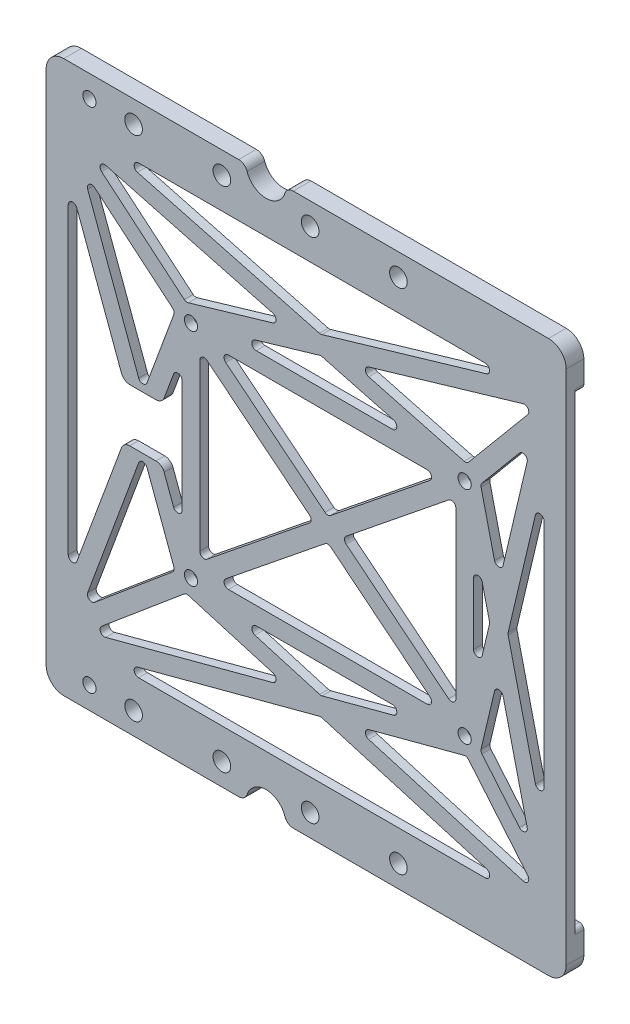
SolidWorks part; units mm, degrees
material "Thornel Mat VMA"
ref_plane "前视基准面" through (0, 0, 0) normal (0, 0, 1) x (1, 0, 0)
ref_plane "上视基准面" through (0, 0, 0) normal (0, 1, 0) x (1, 0, 0)
ref_plane "右视基准面" through (0, 0, 0) normal (1, 0, 0) x (0, 0, -1)
other "Configuration Table"
sketch "草图1" plane through (0, 0, 0) normal (0, 0, 1) x (1, 0, 0)
  line L0 (-59, 57.5) -> (-49, 57.5) construction
  line L1 (-59, -62.5) -> (59, -62.5)
  line L2 (-59, -62.5) -> (-59, 62.5)
  line L3 (-59, 62.5) -> (59, 62.5)
  line L4 (59, -62.5) -> (59, 62.5)
  line L5 (-59, -62.5) -> (59, 62.5) construction
  line L6 (-59, 62.5) -> (59, -62.5) construction
  line L7 (-49, 57.5) -> (-39, 57.5) construction
  line L8 (-39, 57.5) -> (-19, 57.5) construction
  line L9 (-19, 57.5) -> (1, 57.5) construction
  line L10 (0, 0) -> (149.8552, 0) construction
  line L11 (-19, -57.5) -> (1, -57.5) construction
  line L12 (-39, -57.5) -> (-19, -57.5) construction
  line L13 (-49, -57.5) -> (-39, -57.5) construction
  line L14 (1, 57.5) -> (21, 57.5) construction
  circle A0 centre (-49, 57.5) radius 1.5
  circle A1 centre (-39, 57.5) radius 2
  circle A2 centre (-19, 57.5) radius 2
  circle A3 centre (1, 57.5) radius 2
  circle A4 centre (1, -57.5) radius 2
  circle A5 centre (-19, -57.5) radius 2
  circle A6 centre (-39, -57.5) radius 2
  circle A7 centre (-49, -57.5) radius 1.5
  circle A8 centre (21, 57.5) radius 2
  circle A9 centre (21, -57.5) radius 2
  point P0 (0, 0)
  dimension "D6" = 4
  dimension "D7" = 3
  dimension "D1" = 118
  dimension "D2" = 125
  dimension "D3" = 10
  dimension "D4" = 10
  dimension "D5" = 5
  dimension "D8" = 20
extrude "凸台-拉伸1" add sketch "草图1" along normal blind 4
sketch "草图2" plane through (0, 0, 0) normal (0, 0, -1) x (-1, 0, 0)
  line L0 (59, -62.5) -> (-59, -62.5) construction
  line L1 (59, 62.5) -> (58.8, 62.5)
  line L2 (59, 62.5) -> (59, -62.5)
  line L3 (59, -62.5) -> (58.8, -62.5)
  line L4 (58.8, 62.5) -> (58.8, -62.5)
  line L5 (-1, 57.5) -> (19, 57.5) construction
  line L6 (9, 57.5) -> (9, 62.5) construction
  line L7 (-59, 62.5) -> (59, 62.5) construction
  line L8 (0, 0) -> (86.8902, 0) construction
  line L9 (9, -57.5) -> (9, -62.5) construction
  circle A0 centre (9, 62.5) radius 4.5
  circle A1 centre (9, -62.5) radius 4.5
  dimension "D2" = 9
  dimension "D1" = 0.2
extrude "切除-拉伸1" cut sketch "草图2" against normal up to surface (4 mm away) up to face at (0, 0, 4)
sketch "草图3" plane through (0, 0, 0) normal (0, 0, -1) x (-1, 0, 0)
  line L0 (0, 0) -> (-5, 0) construction
  line L5 (-36, -25) -> (26, -25) construction
  line L6 (-36, -25) -> (-36, 25) construction
  line L7 (-36, 25) -> (26, 25) construction
  line L8 (26, -25) -> (26, 25) construction
  line L9 (-36, -25) -> (26, 25) construction
  line L10 (-36, 25) -> (26, -25) construction
  circle A0 centre (26, 25) radius 1.5
  circle A1 centre (26, -25) radius 1.5
  circle A2 centre (-36, -25) radius 1.5
  circle A3 centre (-36, 25) radius 1.5
  point P0 (-5, 0)
  dimension "D4" = 3
  dimension "D1" = 62
  dimension "D2" = 50
  dimension "D3" = 5
extrude "切除-拉伸2" cut sketch "草图3" against normal up to surface (4 mm away) up to face at (-4.45, 0, 4)
fillet "圆角1" radius 2 4 edges at (-4.5, 62.5, 2) (-13.5, 62.5, 2) (-13.5, -62.5, 2) (-4.5, -62.5, 2)
fillet "圆角2" radius 4 4 edges at (59, 62.5, 2) (59, -62.5, 2) (-58.8, -62.5, 2) (-58.8, 62.5, 2)
sketch "草图4" plane through (0, 0, 0) normal (0, 0, -1) x (-1, 0, 0)
  line L0 (-59, -58.5) -> (-59, 58.5) construction
  line L3 (-59, 52.5) -> (58.8, 52.5)
  line L4 (-59, 52.5) -> (-59, -52.5)
  line L6 (-59, -52.5) -> (58.8, -52.5)
  line L7 (58.8, 52.5) -> (58.8, -52.5)
  line L8 (58.8, 58.5) -> (58.8, -58.5) construction
  line L9 (15.1847, 62.5) -> (54.8, 62.5) construction
  line L10 (54.8, -62.5) -> (15.1847, -62.5) construction
  dimension "D1" = 10
  dimension "D2" = 10
extrude "切除-拉伸3" cut sketch "草图4" against normal blind 2
sketch "草图5" plane through (0, 0, 2) normal (0, 0, -1) x (-1, 0, 0)
  line L0 (26, -25) -> (-36, 25) construction
  line L1 (-36, 25) -> (26, 25) construction
  line L2 (26, 25) -> (-36, -25) construction
  line L3 (-36, -25) -> (26, -25) construction
  line L4 (26, -25) -> (58.8, -52.5) construction
  line L5 (26, -25) -> (26, 25) construction
  line L6 (26, 25) -> (58.8, 52.5) construction
  line L7 (58.8, 52.5) -> (-59, 52.5) construction
  line L8 (-59, 52.5) -> (-36, 25) construction
  line L9 (-36, 25) -> (-36, -25) construction
  line L10 (-36, -25) -> (-59, -52.5) construction
  line L12 (-59, 52.5) -> (-59, -52.5) construction
  line L13 (-59, -49.3826) -> (-38, -24.2739)
  line L14 (-38, -24.2739) -> (-38, 24.2739)
  line L15 (-38, 24.2739) -> (-59, 49.3826)
  line L16 (-54.72, 50.5) -> (-35.0654, 27)
  line L17 (-35.0654, 27) -> (25.2725, 27)
  line L18 (25.2725, 27) -> (53.3016, 50.5)
  line L19 (53.3016, 50.5) -> (-54.72, 50.5)
  line L20 (28, 24.0669) -> (53.8, 45.698)
  line L21 (53.8, 45.698) -> (53.8, -45.698)
  line L22 (53.8, -45.698) -> (28, -24.0669)
  line L23 (28, -24.0669) -> (28, 24.0669)
  line L24 (53.3016, -50.5) -> (25.2725, -27)
  line L25 (25.2725, -27) -> (-35.0654, -27)
  line L26 (-35.0654, -27) -> (-54.72, -50.5)
  line L27 (-54.72, -50.5) -> (53.3016, -50.5)
  line L28 (-30.334, -23) -> (-5, -2.5693)
  line L29 (-5, -2.5693) -> (20.334, -23)
  line L30 (20.334, -23) -> (-30.334, -23)
  line L31 (24, 20.8178) -> (24, -20.8178)
  line L32 (24, -20.8178) -> (-1.814, 0)
  line L33 (-1.814, 0) -> (24, 20.8178)
  line L34 (-54, 43.4043) -> (-54, -43.4043)
  line L35 (58.8, -52.5) -> (58.8, 52.5) construction
  line L36 (-59, -52.5) -> (58.8, -52.5) construction
  line L37 (-5, 0) -> (64.3357, 0) construction
  line L38 (-5, 0) -> (-5, -44.1109) construction
  line L39 (-34, -20.8178) -> (-8.186, 0)
  line L40 (-8.186, 0) -> (-34, 20.8178)
  line L41 (-34, 20.8178) -> (-34, -20.8178)
  line L42 (-30.334, 23) -> (-5, 2.5693)
  line L43 (20.334, 23) -> (-30.334, 23)
  line L44 (-5, 2.5693) -> (20.334, 23)
  dimension "D1" = 2
  dimension "D2" = 2
  dimension "D3" = 2
  dimension "D4" = 2
  dimension "D5" = 2
  dimension "D6" = 2
  dimension "D7" = 2
  dimension "D8" = 2
  dimension "D9" = 2
  dimension "D10" = 5
  dimension "D11" = 5
  dimension "D12" = 2
  dimension "D13" = 2
  dimension "D14" = 2
  dimension "D15" = 2
  dimension "D16" = 2
  dimension "D17" = 2
  dimension "D18" = 2
  dimension "D19" = 2
  dimension "D20" = 2
  dimension "D21" = 2
  dimension "D22" = 2
extrude "切除-拉伸4" cut sketch "草图5" against normal blind 2 contours L26 L27 L24 L25 | L15 L34 L13 L14 | L18 L19 L16 L17 | L23 L22 L21 L20 | L40 L41 L39 | L42 L44 L43 | L33 L32 L31 | L30 L29 L28
sketch "草图6" plane through (0, 0, 2) normal (0, 0, -1) x (-1, 0, 0)
  line L0 (53.8, 45.698) -> (28, -24.0669) construction
  line L1 (28, -24.0669) -> (28, 24.0669) construction
  line L2 (28, 24.0669) -> (53.8, -45.698) construction
  line L3 (53.3016, -50.5) -> (-35.0654, -27) construction
  line L4 (-35.0654, -27) -> (25.2725, -27) construction
  line L5 (53.3016, -50.5) -> (25.2725, -27) construction
  line L7 (25.2725, -27) -> (-54.72, -50.5) construction
  line L8 (-36, -25) -> (26, 25) construction
  line L9 (-5, 0) -> (78.3704, 0) construction
  line L10 (-54, -43.4043) -> (-38, 24.2739) construction
  line L11 (-38, 24.2739) -> (-38, -24.2739) construction
  line L12 (-38, -24.2739) -> (-54, 43.4043) construction
  line L13 (-51.135, 39.9788) -> (-43.7387, 8.693)
  line L14 (-38, 24.2739) -> (-54, 43.4043) construction
  line L15 (-43.7387, 8.693) -> (-39.6022, 26.1896)
  line L16 (-39.6022, 26.1896) -> (-51.135, 39.9788)
  line L17 (-54, 34.7113) -> (-54, -34.7113)
  line L18 (-54, -34.7113) -> (-45.7938, 0)
  line L19 (-45.7938, 0) -> (-54, 34.7113)
  line L20 (-54, 43.4043) -> (-54, -43.4043) construction
  line L21 (28, 18.3008) -> (34.7679, 0)
  line L22 (-41.6835, 0) -> (-38, 15.5809)
  line L23 (-38, 15.5809) -> (-38, -15.5809)
  line L24 (-38, -15.5809) -> (-41.6835, 0)
  line L25 (34.7679, 0) -> (28, -18.3008)
  line L26 (28, -18.3008) -> (28, 18.3008)
  line L27 (29.6277, 25.4316) -> (36.9003, 5.7661)
  line L28 (28, 24.0669) -> (53.8, 45.698) construction
  line L29 (36.9003, 5.7661) -> (50.7093, 43.1067)
  line L30 (50.7093, 43.1067) -> (29.6277, 25.4316)
  line L31 (39.0326, 0) -> (53.8, 39.9319)
  line L32 (53.8, 45.698) -> (53.8, -45.698) construction
  line L33 (53.8, 39.9319) -> (53.8, -39.9319)
  line L34 (53.8, -39.9319) -> (39.0326, 0)
  line L35 (-27.2834, -27) -> (-3.4226, -33.3455)
  line L36 (-3.4226, -33.3455) -> (18.1769, -27)
  line L37 (18.1769, -27) -> (-27.2834, -27)
  line L38 (-36.4814, -28.693) -> (-10.8175, -35.5179)
  line L39 (-35.0654, -27) -> (-54.72, -50.5) construction
  line L40 (-10.8175, -35.5179) -> (-52.4087, -47.7365)
  line L41 (-52.4087, -47.7365) -> (-36.4814, -28.693)
  line L42 (4.0259, -35.3263) -> (27.1137, -28.5436)
  line L43 (27.1137, -28.5436) -> (49.6866, -47.4691)
  line L44 (49.6866, -47.4691) -> (4.0259, -35.3263)
  line L45 (-47.6244, -50.5) -> (-3.369, -37.4987)
  line L46 (-54.72, -50.5) -> (53.3016, -50.5) construction
  line L47 (-3.369, -37.4987) -> (45.5196, -50.5)
  line L48 (45.5196, -50.5) -> (-47.6244, -50.5)
  line L49 (36.9003, -5.7661) -> (50.7093, -43.1067)
  line L50 (29.6277, -25.4316) -> (36.9003, -5.7661)
  line L51 (50.7093, -43.1067) -> (29.6277, -25.4316)
  line L52 (-39.6022, -26.1896) -> (-51.135, -39.9788)
  line L53 (-51.135, -39.9788) -> (-43.7387, -8.693)
  line L54 (-43.7387, -8.693) -> (-39.6022, -26.1896)
  line L55 (25.2725, 27) -> (-54.72, 50.5) construction
  line L56 (-35.0654, 27) -> (25.2725, 27) construction
  line L57 (53.3016, 50.5) -> (-35.0654, 27) construction
  line L58 (45.5196, 50.5) -> (-47.6244, 50.5)
  line L59 (-3.369, 37.4987) -> (45.5196, 50.5)
  line L60 (-47.6244, 50.5) -> (-3.369, 37.4987)
  line L61 (49.6866, 47.4691) -> (4.0259, 35.3263)
  line L62 (27.1137, 28.5436) -> (49.6866, 47.4691)
  line L63 (4.0259, 35.3263) -> (27.1137, 28.5436)
  line L64 (-52.4087, 47.7365) -> (-36.4814, 28.693)
  line L65 (-10.8175, 35.5179) -> (-52.4087, 47.7365)
  line L66 (-36.4814, 28.693) -> (-10.8175, 35.5179)
  line L67 (18.1769, 27) -> (-27.2834, 27)
  line L68 (-3.4226, 33.3455) -> (18.1769, 27)
  line L69 (-27.2834, 27) -> (-3.4226, 33.3455)
  line L73 (-1.814, 0) -> (24, -20.8178)
  line L74 (-35.0654, -27) -> (-54.72, -50.5)
  line L75 (25.2725, -27) -> (-35.0654, -27)
  line L76 (53.3016, -50.5) -> (25.2725, -27)
  line L77 (-54.72, -50.5) -> (53.3016, -50.5)
  line L78 (-35.0654, -27) -> (-54.72, -50.5)
  line L79 (25.2725, -27) -> (-35.0654, -27)
  line L80 (53.3016, -50.5) -> (25.2725, -27)
  line L81 (-54.72, -50.5) -> (53.3016, -50.5)
  line L82 (24, 20.8178) -> (-1.814, 0)
  line L83 (24, -20.8178) -> (24, 20.8178)
  line L84 (-1.814, 0) -> (24, -20.8178)
  line L85 (24, 20.8178) -> (-1.814, 0)
  line L86 (24, -20.8178) -> (24, 20.8178)
  line L87 (-30.334, 23) -> (-5, 2.5693)
  line L88 (20.334, 23) -> (-30.334, 23)
  line L89 (-5, 2.5693) -> (20.334, 23)
  line L90 (-30.334, 23) -> (-5, 2.5693)
  line L91 (20.334, 23) -> (-30.334, 23)
  line L92 (-5, 2.5693) -> (20.334, 23)
  line L93 (20.334, -23) -> (-5, -2.5693)
  line L94 (-30.334, -23) -> (20.334, -23)
  line L95 (-5, -2.5693) -> (-30.334, -23)
  line L96 (20.334, -23) -> (-5, -2.5693)
  line L97 (-30.334, -23) -> (20.334, -23)
  line L98 (-5, -2.5693) -> (-30.334, -23)
  line L99 (-8.186, 0) -> (-34, 20.8178)
  line L100 (25.2725, 27) -> (53.3016, 50.5)
  line L101 (-35.0654, 27) -> (25.2725, 27)
  line L102 (-54.72, 50.5) -> (-35.0654, 27)
  line L103 (53.3016, 50.5) -> (-54.72, 50.5)
  line L104 (25.2725, 27) -> (53.3016, 50.5)
  line L105 (-35.0654, 27) -> (25.2725, 27)
  line L106 (-54.72, 50.5) -> (-35.0654, 27)
  line L107 (53.3016, 50.5) -> (-54.72, 50.5)
  line L108 (-38, 24.2739) -> (-54, 43.4043)
  line L109 (-38, -24.2739) -> (-38, 24.2739)
  line L110 (-54, -43.4043) -> (-38, -24.2739)
  line L111 (-54, 43.4043) -> (-54, -43.4043)
  line L112 (-38, 24.2739) -> (-54, 43.4043)
  line L113 (-38, -24.2739) -> (-38, 24.2739)
  line L114 (-54, -43.4043) -> (-38, -24.2739)
  line L115 (-54, 43.4043) -> (-54, -43.4043)
  line L116 (28, -24.0669) -> (53.8, -45.698)
  line L117 (28, 24.0669) -> (28, -24.0669)
  line L118 (53.8, 45.698) -> (28, 24.0669)
  line L119 (53.8, -45.698) -> (53.8, 45.698)
  line L120 (28, -24.0669) -> (53.8, -45.698)
  line L121 (28, 24.0669) -> (28, -24.0669)
  line L122 (53.8, 45.698) -> (28, 24.0669)
  line L123 (53.8, -45.698) -> (53.8, 45.698)
  line L124 (-34, -20.8178) -> (-8.186, 0)
  line L125 (-34, 20.8178) -> (-34, -20.8178)
  line L126 (-8.186, 0) -> (-34, 20.8178)
  line L127 (-34, -20.8178) -> (-8.186, 0)
  line L128 (-34, 20.8178) -> (-34, -20.8178)
  circle A1 centre (26, 25) radius 1.5
  circle A2 centre (26, 25) radius 1.5
  circle A3 centre (-36, -25) radius 1.5
  circle A4 centre (-36, -25) radius 1.5
  circle A5 centre (-36, 25) radius 1.5
  circle A6 centre (-36, 25) radius 1.5
  circle A7 centre (26, -25) radius 1.5
  circle A8 centre (26, -25) radius 1.5
  point P45 (-49.8969, -17.3557)
  line M4 (-54, 43.4043) -> (-38, 24.2739)
  line M5 (-38, 24.2739) -> (-38, -24.2739)
  line M6 (-38, -24.2739) -> (-54, -43.4043)
  line M7 (-54, -43.4043) -> (-54, 43.4043)
  line M8 (53.3016, 50.5) -> (25.2725, 27)
  line M9 (25.2725, 27) -> (-35.0654, 27)
  line M10 (-35.0654, 27) -> (-54.72, 50.5)
  line M11 (-54.72, 50.5) -> (53.3016, 50.5)
  line M15 (-54.72, -50.5) -> (-35.0654, -27)
  line M16 (-35.0654, -27) -> (25.2725, -27)
  line M17 (25.2725, -27) -> (53.3016, -50.5)
  line M18 (53.3016, -50.5) -> (-54.72, -50.5)
  line M33 (53.8, -45.698) -> (28, -24.0669)
  line M34 (28, -24.0669) -> (28, 24.0669)
  line M35 (28, 24.0669) -> (53.8, 45.698)
  line M36 (53.8, 45.698) -> (53.8, -45.698)
  dimension "D1" = 2
  dimension "D2" = 2
  dimension "D3" = 2
  dimension "D4" = 2
  dimension "D5" = 2
  dimension "D6" = 2
  dimension "D7" = 2
  dimension "D8" = 2
  dimension "D9" = 2
  dimension "D10" = 2
  dimension "D11" = 2
  dimension "D12" = 2
  dimension "D13" = 2
  dimension "D14" = 2
  dimension "D15" = 0
  dimension "D16" = 0
  dimension "D17" = 0
  dimension "D18" = 0
  dimension "D19" = 0
  dimension "D20" = 0
  dimension "D21" = 0
  dimension "D22" = 0
  dimension "D23" = 0
  dimension "D24" = 0
  dimension "D25" = 0
  dimension "D26" = 0
extrude "凸台-拉伸2" add sketch "草图6" against normal blind 2 contours L69 L68 L63 L61 L59 L60 L65 L66 M9 M8 M11 M10 | L50 L49 L34 L31 L29 L27 L21 L25 M33 M36 M35 M34 | L45 L47 L44 L42 L36 L35 L38 L40 M18 M17 M16 M15 | L53 L54 L24 L22 L15 L13 L19 L18 M6 M5 M4 M7
fillet "圆角3" radius 1 64 edges at (-50.7093, -43.1067, 3) (-36.9003, -5.7661, 3) (-29.6277, -25.4316, 3) (5, -2.5693, 3) (30.334, -23, 3) (-20.334, -23, 3) (-24, -20.8178, 3) (-24, 20.8178, 3) (1.814, 0, 3) (59, 52.5, 1) (-58.8, 52.5, 1) (-58.8, -52.5, 1) (59, -52.5, 1) (5, 2.5693, 3) (-20.334, 23, 3) (30.334, 23, 3) (34, 20.8178, 3) (34, -20.8178, 3) (8.186, 0, 3) (3.369, 37.4987, 3) (-45.5196, 50.5, 3) (47.6244, 50.5, 3) (10.8175, 35.5179, 3) (52.4087, 47.7365, 3) (36.4814, 28.693, 3) (3.4226, 33.3455, 3) (27.2834, 27, 3) (-18.1769, 27, 3) (-4.0259, 35.3263, 3) (-27.1137, 28.5436, 3) (-49.6866, 47.4691, 3) (-39.0326, 0, 3) (-53.8, 39.9319, 3) (-36.9003, 5.7661, 3) (-50.7093, 43.1067, 3) (-29.6277, 25.4316, 3) (-34.7679, 0, 3) (-28, 18.3008, 3) (-28, -18.3008, 3) (3.369, -37.4987, 3) (47.6244, -50.5, 3) (-45.5196, -50.5, 3) (-4.0259, -35.3263, 3) (-49.6866, -47.4691, 3) (-27.1137, -28.5436, 3) (3.4226, -33.3455, 3) (-18.1769, -27, 3) (27.2834, -27, 3) (10.8175, -35.5179, 3) (36.4814, -28.693, 3) (52.4087, -47.7365, 3) (45.7938, 0, 3) (54, 34.7113, 3) (54, -34.7113, 3) (43.7387, -8.693, 3) (51.135, -39.9788, 3) (39.6022, -26.1896, 3) (41.6835, 0, 3) (38, -15.5809, 3) (38, 15.5809, 3) (43.7387, 8.693, 3) (39.6022, 26.1896, 3) (51.135, 39.9788, 3) (-53.8, -39.9319, 3)
sketch "草图7" plane through (0, 0, 2) normal (0, 0, -1) x (-1, 0, 0)
  line L1 (39.1609, 0.3469) -> (51.8621, 34.6916) construction
  line L2 (32.549, -6) -> (41.2515, -6)
  line L3 (32.549, -6) -> (32.549, 6)
  line L4 (32.549, 6) -> (41.2515, 6)
  line L5 (41.2515, -6) -> (41.2515, 6)
  line L6 (32.549, -6) -> (41.2515, 6) construction
  line L7 (32.549, 6) -> (41.2515, -6) construction
  line L8 (36.9003, 0) -> (0, 0) construction
  line L9 (29.9379, 13.0605) -> (34.6396, 0.3469) construction
  point P2 (36.9003, 0)
  dimension "D1" = 12
extrude "切除-拉伸5" cut sketch "草图7" against normal blind 10
fillet "圆角4" radius 2 4 edges at (-41.2515, 6, 3) (-41.2515, -6, 3) (-32.549, -6, 3) (-32.549, 6, 3)
